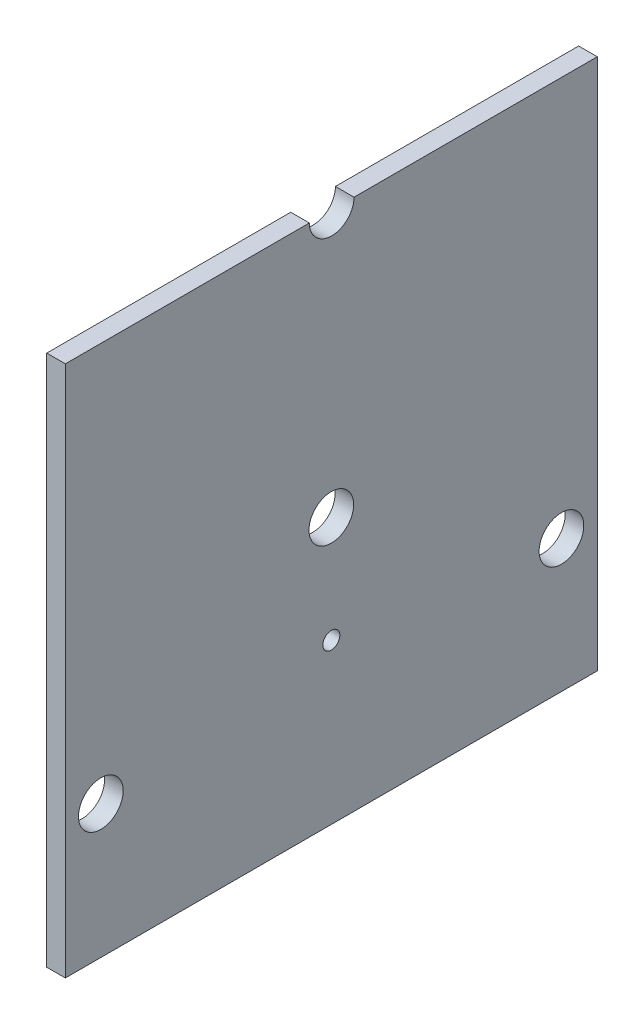
SolidWorks part; units mm, degrees
material "Tungsten"
ref_plane "Ebene vorne" through (0, 0, 0) normal (0, 0, 1) x (1, 0, 0)
ref_plane "Ebene oben" through (0, 0, 0) normal (0, 1, 0) x (1, 0, 0)
ref_plane "Ebene rechts" through (0, 0, 0) normal (1, 0, 0) x (0, 0, -1)
sketch "Sketch2" plane through (0, 0, 0) normal (1, 0, 0) x (0, 0, -1)
  line L0 (0, 50) -> (0, -50) construction
  line L1 (-50, 50) -> (50, 50)
  line L2 (-50, 50) -> (-50, -50)
  line L3 (-50, -50) -> (50, -50)
  line L4 (50, 50) -> (50, -50)
  line L5 (-50, 0) -> (50, 0) construction
  line L7 (-50, 50) -> (50, -50) construction
  circle A0 centre (0, 0) radius 4.2
  point P19 (0, 0)
  point P20 (0, 0)
  point P21 (0, 0)
  dimension "D3" = 8.4
  dimension "D1" = 100
  dimension "D2" = 100
extrude "Boss-Extrude1" add sketch "Sketch2" along normal blind 3.5
sketch "Sketch3" plane through (0, 0, 0) normal (-1, 0, 0) x (0, 0, 1)
  circle A0 centre (43.337, -24.9381) radius 4.2
  circle A1 centre (-43.2655, -25.0619) radius 4.2
  circle A2 centre (-0.0715, 49.9999) radius 4.2
  point P9 (0, 0)
  dimension "D1" = 8.4
  dimension "D2" = 50
  dimension "D3" = 3
extrude "Cut-Extrude1" cut sketch "Sketch3" against normal through all
sketch "Sketch4" plane through (0, 0, 0) normal (-1, 0, 0) x (0, 0, 1)
  circle A0 centre (0, -20) radius 1.6
  dimension "D1" = 3.2
  dimension "D2" = 20
extrude "Cut-Extrude2" cut sketch "Sketch4" against normal through all
